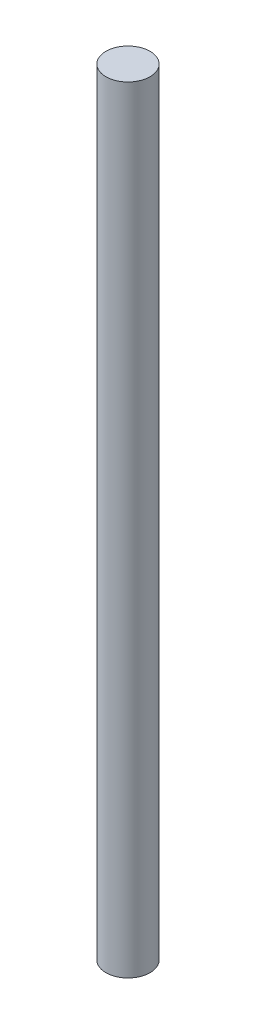
SolidWorks part; units mm, degrees
ref_plane "Front" through (0, 0, 0) normal (0, 0, 1) x (1, 0, 0)
ref_plane "Top" through (0, 0, 0) normal (0, 1, 0) x (1, 0, 0)
ref_plane "Right" through (0, 0, 0) normal (1, 0, 0) x (0, 0, -1)
sketch "Sketch1" plane through (0, 0, 0) normal (0, 1, 0) x (1, 0, 0)
  circle A0 centre (-41.1648, -11.4406) radius 1.5875
extrude "Boss-Extrude1" add sketch "Sketch1" along normal blind 55.88
